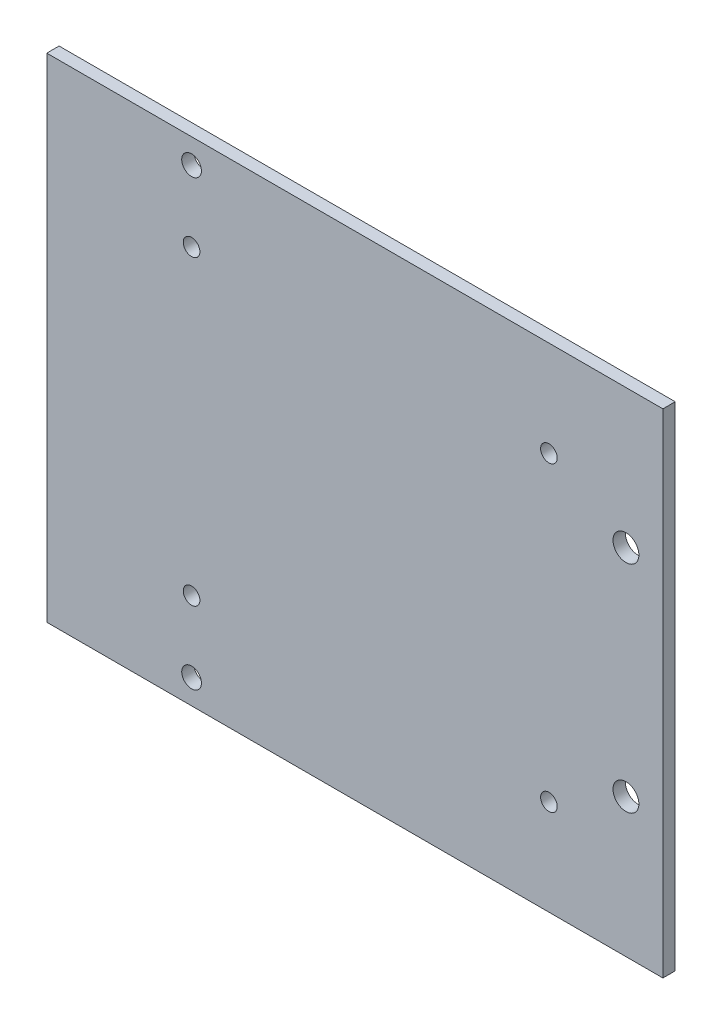
SolidWorks part; units mm, degrees
ref_plane "前视基准面" through (0, 0, 0) normal (0, 0, 1) x (1, 0, 0)
ref_plane "上视基准面" through (0, 0, 0) normal (0, 1, 0) x (1, 0, 0)
ref_plane "右视基准面" through (0, 0, 0) normal (1, 0, 0) x (0, 0, -1)
sketch "草图1" plane through (0, 0, 0) normal (0, 0, 1) x (1, 0, 0)
  line L1 (-50, 40) -> (50, 40)
  line L2 (-50, 40) -> (-50, -40)
  line L3 (-50, -40) -> (50, -40)
  line L4 (50, 40) -> (50, -40)
  line L5 (-50, 40) -> (50, -40) construction
  line L6 (-50, -40) -> (50, 40) construction
  point P0 (0, 0)
  dimension "D1" = 80
  dimension "D2" = 100
extrude "凸台-拉伸1" add sketch "草图1" along normal blind 2
sketch "草图3" plane through (0, 0, 2) normal (0, 0, 1) x (1, 0, 0)
  line L0 (-50, 0) -> (50, 0) construction
  line L1 (-26.5, -40) -> (-26.5, 40) construction
  line L2 (2.5, -40) -> (2.5, 40) construction
  line L4 (50, -40) -> (50, 40)
  line L5 (50, 40) -> (-50, 40)
  line L6 (-50, 40) -> (-50, -40)
  line L7 (-50, -40) -> (50, -40)
  line L8 (50, -40) -> (50, 40)
  line L9 (50, 40) -> (-50, 40)
  line L10 (-50, 40) -> (-50, -40)
  line L11 (-50, -40) -> (50, -40)
  circle A0 centre (-26.5, -24.5) radius 1.35
  circle A1 centre (-26.5, 24.5) radius 1.35
  circle A2 centre (31.5, 24.5) radius 1.35
  circle A3 centre (31.5, -24.5) radius 1.35
  dimension "D3" = 2.7
  dimension "D4" = 49
  dimension "D5" = 58
  dimension "D2" = 23.5
  dimension "D1" = 0
extrude "切除-拉伸1" cut sketch "草图3" against normal through all contours A0 | A1 | A2 | A3
sketch "草图4" plane through (0, 0, 0) normal (0, 0, -1) x (-1, 0, 0)
  circle A0 centre (26.5, -36) radius 1.6 construction
  circle A1 centre (26.5, -36) radius 1.6
extrude "切除-拉伸2" cut sketch "草图4" against normal through all
sketch "草图5" plane through (0, 0, 2) normal (0, 0, 1) x (1, 0, 0)
  line L0 (-26.5, 23.15) -> (-26.5, 40) construction
  line L4 (50, -40) -> (50, 40)
  line L5 (50, 40) -> (-50, 40)
  line L6 (-50, 40) -> (-50, -40)
  line L7 (-50, -40) -> (50, -40)
  line L8 (50, -40) -> (50, 40)
  line L9 (50, 40) -> (-50, 40)
  line L10 (-50, 40) -> (-50, -40)
  line L11 (-50, -40) -> (50, -40)
  circle A0 centre (-26.5, 24.5) radius 1.35 construction
  circle A1 centre (-26.5, 36) radius 1.6
  dimension "D2" = 3.2
  dimension "D3" = 11.5
  dimension "D1" = 0
extrude "切除-拉伸3" cut sketch "草图5" against normal through all contours A1
sketch "草图7" plane through (0, 0, 2) normal (0, 0, 1) x (1, 0, 0)
  line L0 (50, 0) -> (-50, 0) construction
  line L1 (44, 40) -> (44, -40) construction
  line L4 (50, -40) -> (50, 40)
  line L5 (50, 40) -> (-50, 40)
  line L6 (-50, 40) -> (-50, -40)
  line L7 (-50, -40) -> (50, -40)
  line L8 (50, -40) -> (50, 40)
  line L9 (50, 40) -> (-50, 40)
  line L10 (-50, 40) -> (-50, -40)
  line L11 (-50, -40) -> (50, -40)
  circle A0 centre (44, 17.5) radius 2.1
  circle A1 centre (44, -17.5) radius 2.1
  dimension "D3" = 4.2
  dimension "D4" = 35
  dimension "D2" = 6
  dimension "D1" = 0
extrude "切除-拉伸5" cut sketch "草图7" against normal blind 10 contours A0 | A1
